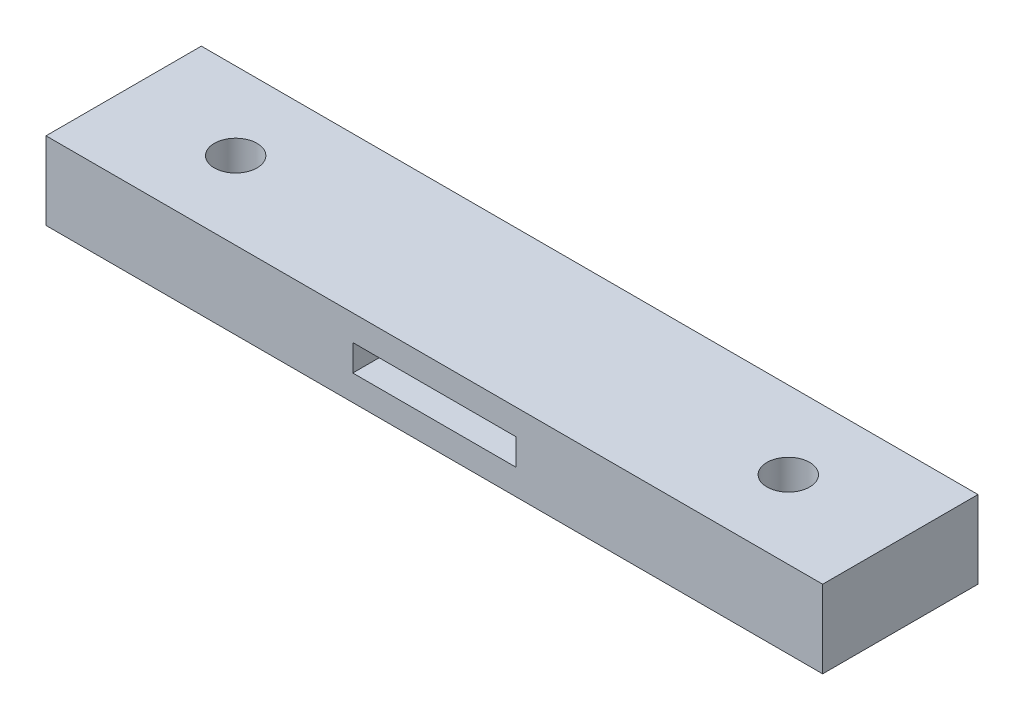
SolidWorks part; units mm, degrees
ref_plane "Front Plane" through (0, 0, 0) normal (0, 0, 1) x (1, 0, 0)
ref_plane "Top Plane" through (0, 0, 0) normal (0, 1, 0) x (1, 0, 0)
ref_plane "Right Plane" through (0, 0, 0) normal (1, 0, 0) x (0, 0, -1)
sketch "Sketch2" plane through (0, 0, 0) normal (0, 0, 1) x (1, 0, 0)
  line L1 (-63.5, -6.35) -> (63.5, -6.35)
  line L2 (-63.5, -6.35) -> (-63.5, 6.35)
  line L3 (-63.5, 6.35) -> (63.5, 6.35)
  line L4 (63.5, -6.35) -> (63.5, 6.35)
  line L5 (-63.5, -6.35) -> (63.5, 6.35) construction
  line L6 (-63.5, 6.35) -> (63.5, -6.35) construction
  line L7 (-13.335, -2.159) -> (13.335, -2.159)
  line L8 (-13.335, -2.159) -> (-13.335, 2.159)
  line L9 (-13.335, 2.159) -> (13.335, 2.159)
  line L10 (13.335, -2.159) -> (13.335, 2.159)
  line L11 (-13.335, -2.159) -> (13.335, 2.159) construction
  line L12 (-13.335, 2.159) -> (13.335, -2.159) construction
  point P0 (0, 0)
  point P6 (0, 0)
  dimension "D1" = 127
  dimension "D2" = 12.7
  dimension "D3" = 26.67
  dimension "D4" = 4.318
extrude "Boss-Extrude1" add sketch "Sketch2" along normal blind 25.4
sketch "Sketch3" plane through (0, 6.35, 0) normal (0, 1, 0) x (1, 0, 0)
  line L0 (-63.5, -12.7) -> (63.5, -12.7) construction
  line L1 (-63.5, -25.4) -> (-63.5, 0) construction
  line L2 (63.5, -25.4) -> (63.5, 0) construction
  line L3 (0, 0) -> (0, -25.4) construction
  line L4 (63.5, -25.4) -> (-63.5, -25.4) construction
  circle A0 centre (45.1845, -12.7) radius 3.4925
  circle A1 centre (-45.1845, -12.7) radius 3.4925
  dimension "D1" = 6.985
  dimension "1.5in" = 45.1845
  dimension "D2" = 45.1845
extrude "Cut-Extrude1" cut sketch "Sketch3" against normal through all
equation "\"D2@Sketch3\"=\"1.5in@Sketch3\""
